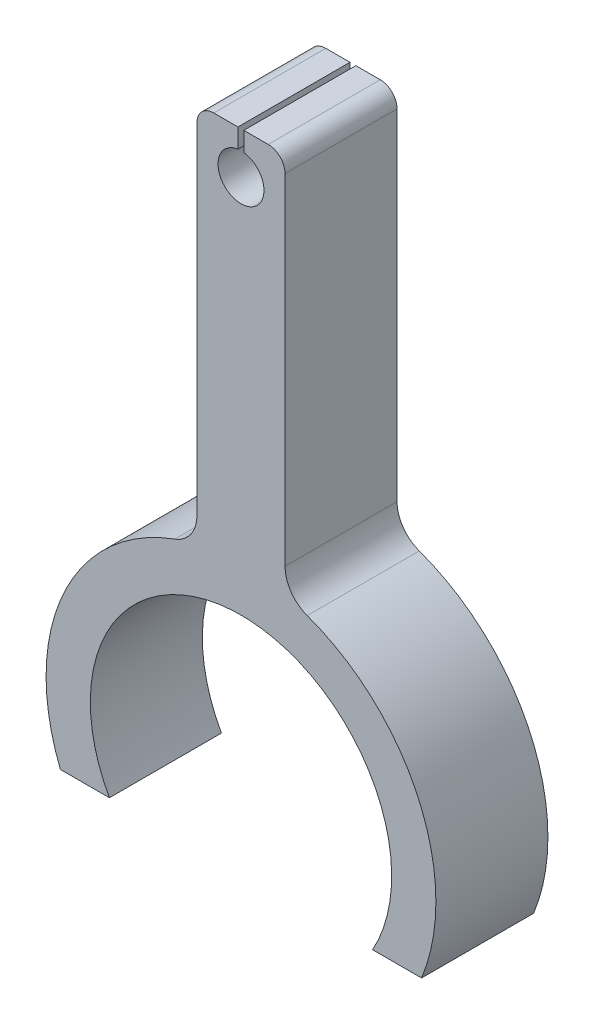
SolidWorks part; units mm, degrees
ref_plane "Front Plane" through (0, 0, 0) normal (0, 0, 1) x (1, 0, 0)
ref_plane "Top Plane" through (0, 0, 0) normal (0, 1, 0) x (1, 0, 0)
ref_plane "Right Plane" through (0, 0, 0) normal (1, 0, 0) x (0, 0, -1)
sketch "Sketch1" plane through (0, 0, 0) normal (0, 0, 1) x (1, 0, 0)
  line L4 (0, 0) -> (0, 51.0523) construction
  line L5 (3.9329, 51.0523) -> (3.9329, 16.9497)
  line L6 (-3.9329, 51.0523) -> (3.9329, 51.0523)
  line L7 (-3.9329, 51.0523) -> (-3.9329, 16.9497)
  line L8 (-16.12, -6.5503) -> (-11.7472, -6.5503)
  line L9 (11.7472, -6.5503) -> (16.12, -6.5503)
  arc A0 (11.7472, -6.5503) -> (-11.7472, -6.5503) centre (0, 0) ccw
  arc A2 (-3.9329, 16.9497) -> (-16.12, -6.5503) centre (0, 0) ccw
  arc A3 (16.12, -6.5503) -> (3.9329, 16.9497) centre (0, 0) ccw
  circle A4 centre (0, 0) radius 17.4 construction
  circle A6 centre (0, 0) radius 13.45 construction
  point P10 (17.4, 0)
  point P13 (12.8623, 3.9324)
  dimension "D1" = 26.9
  dimension "D3" = 23.5
  dimension "D2" = 3.95
extrude "Boss-Extrude1" add sketch "Sketch1" along normal blind 10 contours L5 A3 L9 A0 L8 A2 L7 L6
fillet "Fillet1" radius 1.5 2 edges at (-3.9329, 51.0523, 5) (3.9329, 51.0523, 5)
fillet "Fillet2" radius 3 2 edges at (-3.9329, 16.9497, 5) (3.9329, 16.9497, 5)
sketch "Sketch3" plane through (0, 0, 10) normal (0, 0, 1) x (1, 0, 0)
  line L4 (-0.2693, 49.3312) -> (-0.2693, 51.0523)
  line L7 (-2.4329, 51.0523) -> (2.4329, 51.0523) construction
  line L8 (-0.2693, 51.0523) -> (0.2512, 51.0523)
  line L9 (0.2512, 51.0523) -> (0.2512, 49.3335)
  arc A0 (-0.2693, 49.3312) -> (0.2512, 49.3335) centre (0, 47.299) ccw
  dimension "D1" = 4.1
extrude "Cut-Extrude1" cut sketch "Sketch3" against normal blind 10
